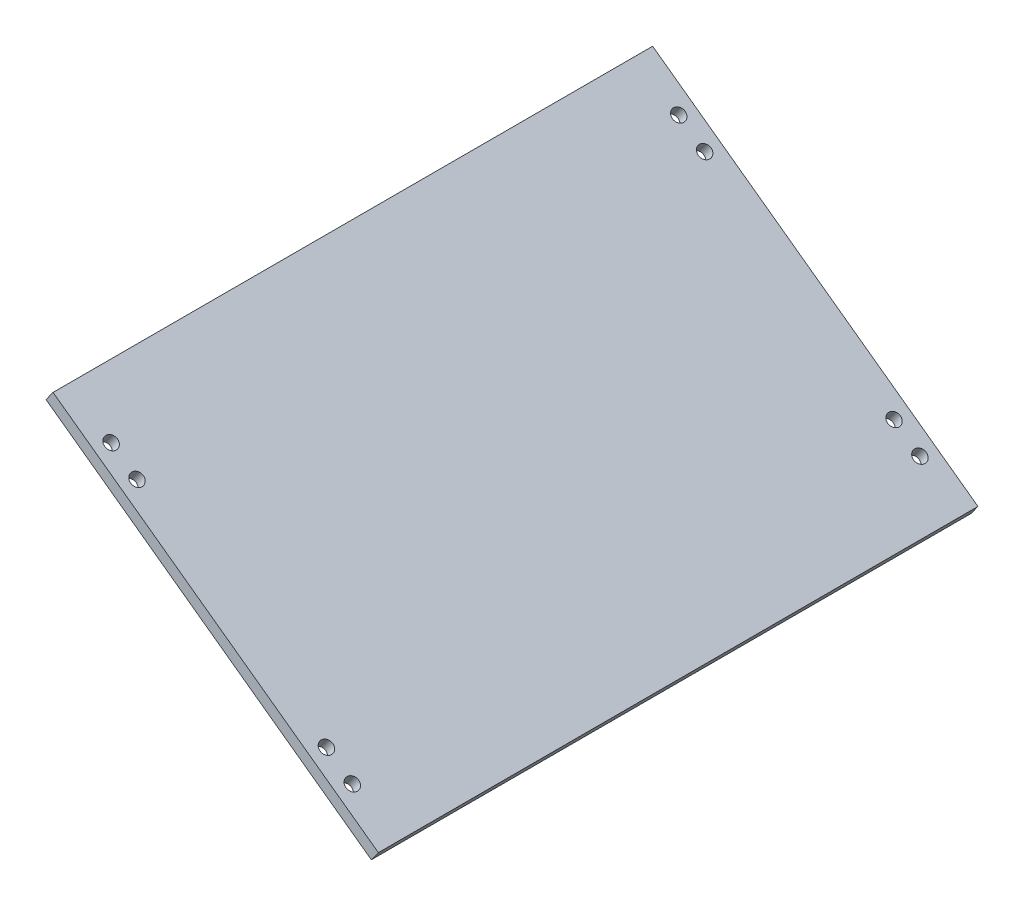
SolidWorks part; units mm, degrees
ref_plane "前视基准面" through (0, 0, 0) normal (0, 0, 1) x (1, 0, 0)
ref_plane "上视基准面" through (0, 0, 0) normal (0, 1, 0) x (1, 0, 0)
ref_plane "右视基准面" through (0, 0, 0) normal (1, 0, 0) x (0, 0, -1)
other "Configuration Table"
ref_plane "基准面1" through (11.3221, 115.3599, -47.1117) normal (0.8096, -0.587, 0) x (0, 0, -1)
sketch "草图2" plane through (58.724, 80.9896, 0) normal (0.587, 0.8096, 0) x (0.8096, -0.587, 0)
  line L0 (-58.5513, 47.1117) -> (41.9497, 47.1117)
  line L1 (-58.5513, 47.1117) -> (-58.5513, -102.8399)
  line L2 (41.9497, 47.1117) -> (41.9497, -102.8399)
  line L3 (-58.5513, -102.8399) -> (41.9497, -102.8399)
  line L4 (-58.5513, 47.1117) -> (41.9497, 47.1117) construction
  line L6 (64.8789, -27.8641) -> (-85.9639, -27.8641) construction
  circle A0 centre (-45.5513, 43.1117) radius 1.6
  circle A1 centre (-37.5513, 43.1117) radius 1.6
  circle A2 centre (20.9497, 43.1117) radius 1.6
  circle A3 centre (28.9497, 43.1117) radius 1.6
  circle A4 centre (28.9497, -98.8399) radius 1.6
  circle A5 centre (20.9497, -98.8399) radius 1.6
  circle A6 centre (-37.5513, -98.8399) radius 1.6
  circle A7 centre (-45.5513, -98.8399) radius 1.6
  dimension "D3" = 3.2
  dimension "D4" = 3.2
  dimension "D5" = 3.2
  dimension "D6" = 3.2
  dimension "D1" = 149.9516
  dimension "D2" = 100.5011
  dimension "D7" = 74.9758
extrude "凸台-拉伸1" add sketch "草图2" against normal blind 3
